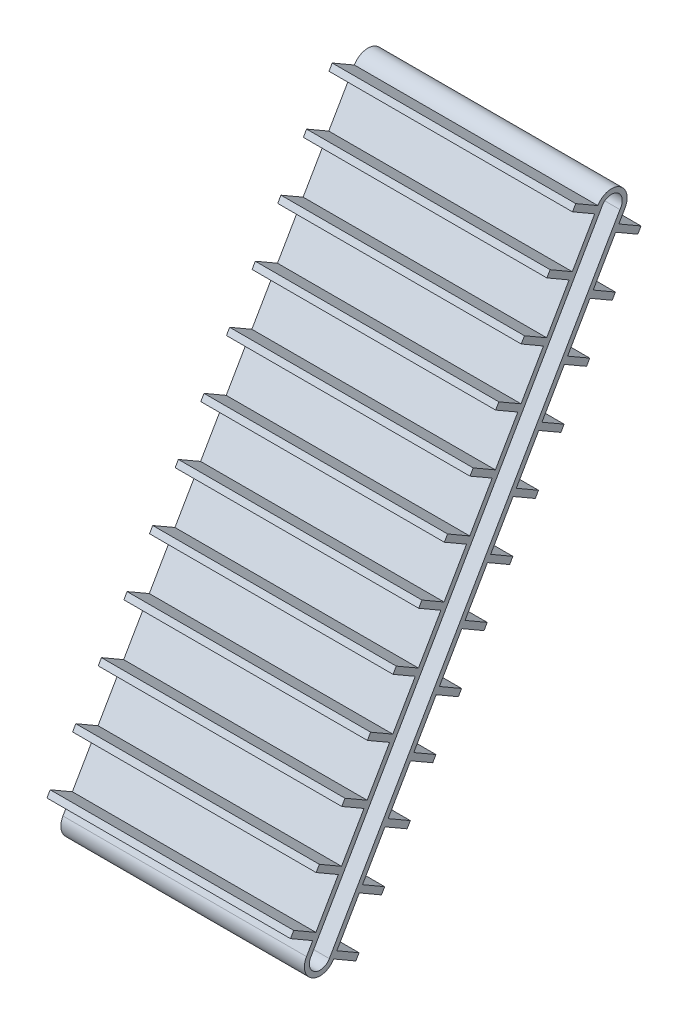
SolidWorks part; units mm, degrees
ref_plane "Front Plane" through (0, 0, 0) normal (0, 0, 1) x (1, 0, 0)
ref_plane "Top Plane" through (0, 0, 0) normal (0, 1, 0) x (1, 0, 0)
ref_plane "Right Plane" through (0, 0, 0) normal (1, 0, 0) x (0, 0, -1)
sketch "Sketch1" plane through (0, 0, 0) normal (1, 0, 0) x (0, 0, -1)
  line L0 (0, 0) -> (0, -2846.1) construction
  line L1 (0, -2846.1) -> (-3338.6788, -2846.1) construction
  line L2 (0, 0) -> (-1643.1966, -2846.1) construction
  line L3 (-1427.5584, -2325.8036) -> (-66.7699, 30.485)
  line L4 (-1300.4303, -2399.2114) -> (63.5663, -36.7)
  line L5 (-1407.2979, -2337.5114) -> (-46.8093, 18.924)
  line L6 (-1320.6953, -2387.5114) -> (39.7933, -31.076)
  arc A1 (-1407.2979, -2337.5114) -> (-1320.6953, -2387.5114) centre (-1363.9966, -2362.5114) ccw
  arc A2 (-1427.5584, -2325.8036) -> (-1300.4303, -2399.2114) centre (-1363.9966, -2362.5114) ccw
  arc A4 (39.7933, -31.076) -> (-46.8093, 18.924) centre (0, 0) ccw
  arc A5 (63.5663, -36.7) -> (-66.7699, 30.485) centre (0, 0) ccw
  dimension "D1" = 60
  dimension "D3" = 100
  dimension "D5" = 146.8
  dimension "D6" = 73.4
  dimension "D7" = 73.4
  dimension "D2" = 2846.1
  dimension "D4" = 558.4
extrude "Boss-Extrude1" add sketch "Sketch1" along normal blind 1140 contours L3 A5 L4 A2 | L5 A4 L6 A1
sketch "Sketch2" plane through (0, 36.5408, 63.2726) normal (0, 0.5001, 0.866) x (1, 0, 0)
  line L0 (1140, -2727.9932) -> (1140, -6.9931) construction
  line L1 (0, 0) -> (1140, 0)
  line L2 (0, 0) -> (0, -30)
  line L3 (0, -30) -> (1140, -30)
  line L4 (1140, 0) -> (1140, -30)
  dimension "D1" = 30
extrude "Boss-Extrude2" add sketch "Sketch2" along normal blind 120
pattern_linear "LPattern1" count 12 spacing 240 along (0, -0.866, 0.5001) of "Boss-Extrude2"
sketch "Sketch3" plane through (0, -36.7, -63.5663) normal (0, -0.5, -0.866) x (-1, 0, 0)
  line L0 (0, -2727.9932) -> (0, 0) construction
  line L1 (-1140, -2727.9932) -> (0, -2727.9932)
  line L2 (-1140, -2727.9932) -> (-1140, -2697.9932)
  line L3 (-1140, -2697.9932) -> (0, -2697.9932)
  line L4 (0, -2727.9932) -> (0, -2697.9932)
  dimension "D1" = 30
extrude "Boss-Extrude3" add sketch "Sketch3" along normal blind 120
pattern_linear "LPattern2" count 12 spacing 240 along (0, 0.866, -0.5) of "Boss-Extrude3"
